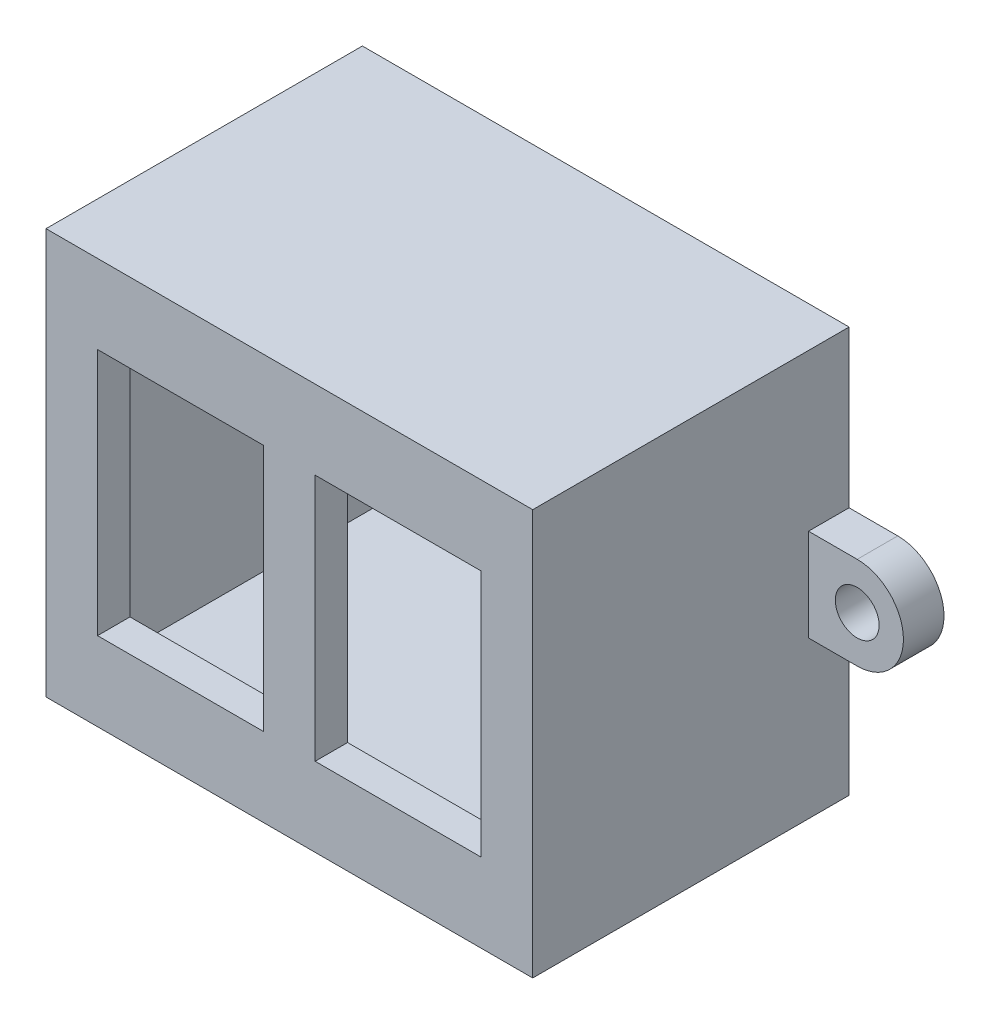
SolidWorks part; units mm, degrees
material "PET"
ref_plane "Front Plane" through (0, 0, 0) normal (0, 0, 1) x (1, 0, 0)
ref_plane "Top Plane" through (0, 0, 0) normal (0, 1, 0) x (1, 0, 0)
ref_plane "Right Plane" through (0, 0, 0) normal (1, 0, 0) x (0, 0, -1)
sketch "Sketch1" plane through (0, 0, 0) normal (0, 0, 1) x (1, 0, 0)
  line L0 (4.0333, 15.875) -> (0, 15.875) construction
  line L1 (0, 0) -> (38.1, 0)
  line L2 (0, 0) -> (0, 31.75)
  line L3 (0, 31.75) -> (38.1, 31.75)
  line L4 (38.1, 0) -> (38.1, 31.75)
  line L5 (4.0333, 6.175) -> (17.0333, 6.175)
  line L6 (4.0333, 6.175) -> (4.0333, 25.575)
  line L7 (4.0333, 25.575) -> (17.0333, 25.575)
  line L8 (17.0333, 6.175) -> (17.0333, 25.575)
  line L9 (21.0667, 6.175) -> (34.0667, 6.175)
  line L10 (21.0667, 6.175) -> (21.0667, 25.575)
  line L11 (21.0667, 25.575) -> (34.0667, 25.575)
  line L12 (34.0667, 6.175) -> (34.0667, 25.575)
  line L13 (17.0333, 15.875) -> (21.0667, 15.875) construction
  line L14 (34.0667, 15.875) -> (38.1, 15.875) construction
  dimension "D1" = 38.1
  dimension "D2" = 31.75
  dimension "D3" = 19.4
  dimension "D4" = 13
  dimension "D5" = 13
  dimension "D6" = 19.4
extrude "Boss-Extrude1" add sketch "Sketch1" along normal blind 2.54
sketch "Sketch2" plane through (0, 0, 0) normal (0, 0, -1) x (-1, 0, 0)
  line L0 (0, 31.75) -> (0, 0) construction
  line L1 (0, 0) -> (-38.1, 0) construction
  line L2 (-38.1, 0) -> (-38.1, 31.75) construction
  line L3 (-38.1, 31.75) -> (0, 31.75) construction
  line L4 (0, 31.75) -> (0, 0)
  line L5 (0, 0) -> (-38.1, 0)
  line L6 (-38.1, 0) -> (-38.1, 31.75)
  line L7 (-38.1, 31.75) -> (0, 31.75)
  line L8 (-35.56, 2.54) -> (-35.56, 29.21)
  line L9 (-35.56, 29.21) -> (-2.54, 29.21)
  line L10 (-2.54, 29.21) -> (-2.54, 2.54)
  line L11 (-2.54, 2.54) -> (-35.56, 2.54)
  dimension "D1" = 2.54
extrude "Boss-Extrude2" add sketch "Sketch2" along normal blind 22.225
sketch "Sketch3" plane through (0, 0, -22.225) normal (0, 0, -1) x (-1, 0, 0)
  line L0 (-41.91, 15.875) -> (-38.1, 15.875) construction
  line L1 (-38.1, 31.75) -> (-38.1, 0) construction
  line L2 (3.81, 15.875) -> (0, 15.875) construction
  line L3 (0, 0) -> (0, 31.75) construction
  line L4 (-41.91, 19.4945) -> (-38.1, 19.4945)
  line L5 (-38.1, 19.4945) -> (-38.1, 12.2555)
  line L6 (-38.1, 12.2555) -> (-41.91, 12.2555)
  line L7 (3.81, 12.2555) -> (0, 12.2555)
  line L8 (0, 12.2555) -> (0, 19.4945)
  line L9 (0, 19.4945) -> (3.81, 19.4945)
  circle A0 centre (-41.91, 15.875) radius 1.7145
  circle A1 centre (3.81, 15.875) radius 1.7145
  arc A2 (-41.91, 19.4945) -> (-41.91, 12.2555) centre (-41.91, 15.875) ccw
  arc A3 (3.81, 12.2555) -> (3.81, 19.4945) centre (3.81, 15.875) ccw
  point P20 (0, 12.2555)
  dimension "D1" = 3.429
  dimension "D2" = 3.429
  dimension "D5" = 1.905
  dimension "D6" = 1.905
  dimension "D3" = 3.81
  dimension "D4" = 3.81
extrude "Boss-Extrude3" add sketch "Sketch3" against normal blind 3.175
sketch "Sketch4" plane through (0, 0, 0) normal (0, -1, 0) x (1, 0, 0)
  line L0 (19.05, -22.225) -> (19.05, -19.05) construction
  line L1 (38.1, -22.225) -> (0, -22.225) construction
  line L2 (22.225, -19.05) -> (22.225, -22.225)
  line L3 (22.225, -22.225) -> (15.875, -22.225)
  line L4 (15.875, -22.225) -> (15.875, -19.05)
  arc A0 (22.225, -19.05) -> (15.875, -19.05) centre (19.05, -19.05) ccw
  dimension "D2" = 6.35
  dimension "D1" = 3.175
extrude "Cut-Extrude1" cut sketch "Sketch4" against normal up to next
